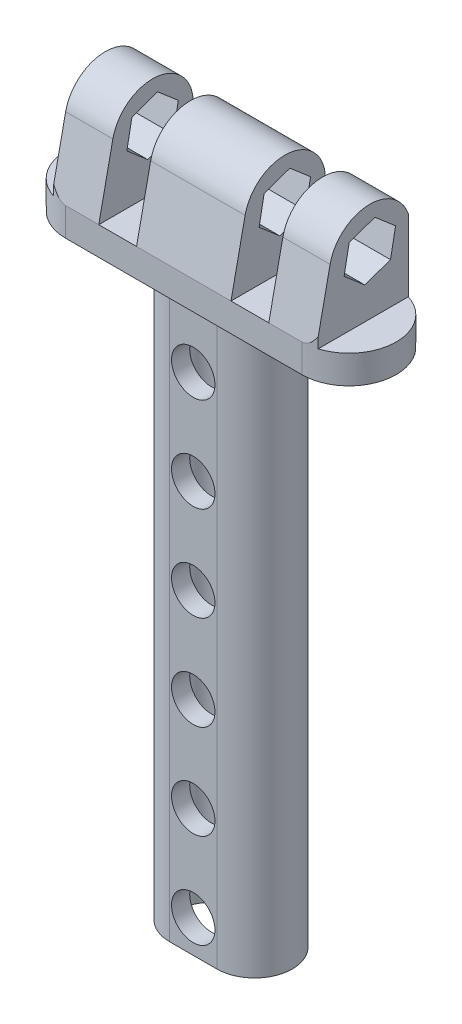
SolidWorks part; units mm, degrees
ref_plane "前视基准面" through (0, 0, 0) normal (0, 0, 1) x (1, 0, 0)
ref_plane "上视基准面" through (0, 0, 0) normal (0, 1, 0) x (1, 0, 0)
ref_plane "右视基准面" through (0, 0, 0) normal (1, 0, 0) x (0, 0, -1)
other "Configuration Table"
sketch "草图1" plane through (0, 0, 0) normal (0, 1, 0) x (1, 0, 0)
  line L0 (-12.5, 0) -> (12.5, 0) construction
  line L1 (-12.5, 5) -> (12.5, 5)
  line L2 (-12.5, -5) -> (12.5, -5)
  arc A0 (-12.5, 5) -> (-12.5, -5) centre (-12.5, 0) ccw
  arc A1 (12.5, -5) -> (12.5, 5) centre (12.5, 0) ccw
  point P2 (0, 0)
extrude "凸台-拉伸1" add sketch "草图1" along normal blind 3
sketch "草图2" plane through (0, 0, 0) normal (1, 0, 0) x (0, 0, -1)
  line L0 (-5, 3) -> (-3.5084, 10.1121)
  line L2 (5, 9.2295) -> (5, 3)
  line L3 (-5, 3) -> (5, 3)
  line L5 (2.889, 7.3476) -> (3.4243, 10.1843)
  line L6 (3.4243, 10.1843) -> (1.2353, 12.0662)
  line L7 (1.2353, 12.0662) -> (-1.489, 11.1114)
  line L8 (-1.489, 11.1114) -> (-2.0243, 8.2747)
  line L9 (-2.0243, 8.2747) -> (0.1648, 6.3928)
  line L10 (0.1648, 6.3928) -> (2.889, 7.3476)
  arc A1 (5, 9.2295) -> (-3.5084, 10.1121) centre (0.7, 9.2295) ccw
  circle A2 centre (0.7, 9.2295) radius 2.5 construction
  point P8 (5, 13.9205)
  point P16 (0, 0)
  point P17 (0, 0)
  point P18 (0, 0)
  dimension "D1" = 2.5
extrude "凸台-拉伸2" add sketch "草图2" along normal mid plane 28
sketch "草图3" plane through (0, 0, 0) normal (0, -1, 0) x (1, 0, 0)
  line L0 (-2.5, 0) -> (2.5, 0) construction
  line L1 (-2.5, 4) -> (2.5, 4)
  line L2 (-2.5, -4) -> (2.5, -4)
  line L3 (-2.7056, 0) -> (2.7056, 0) construction
  line L4 (-2.7056, 2.072) -> (2.7056, 2.072)
  line L5 (-2.7056, -2.072) -> (2.7056, -2.072)
  arc A0 (-2.5, 4) -> (-2.5, -4) centre (-2.5, 0) ccw
  arc A1 (2.5, -4) -> (2.5, 4) centre (2.5, 0) ccw
  arc A2 (-2.7056, 2.072) -> (-2.7056, -2.072) centre (-2.7056, 0) ccw
  arc A3 (2.7056, -2.072) -> (2.7056, 2.072) centre (2.7056, 0) ccw
  point P2 (0, 0)
  point P10 (0, 0)
  dimension "D1" = 8
  dimension "D2" = 5
extrude "凸台-拉伸3" add sketch "草图3" along normal blind 60
sketch "草图4" plane through (0, 0, 4) normal (0, 0, 1) x (1, 0, 0)
  circle A0 centre (0, -6.528) radius 2.3
  circle A1 centre (0, -16.528) radius 2.3
  circle A2 centre (0, -26.528) radius 2.3
  circle A3 centre (0, -36.528) radius 2.3
  circle A4 centre (0, -46.528) radius 2.3
  circle A5 centre (0, -56.528) radius 2.3
  dimension "D1" = 6
extrude "切除-拉伸1" cut sketch "草图4" against normal blind 60
sketch "草图6" plane through (0, 0, -5) normal (0, 0, -1) x (-1, 0, 0)
  line L0 (14, 13.5295) -> (-14, 13.5295) construction
  line L1 (-9, 13.5295) -> (-5, 13.5295)
  line L2 (-9, 13.5295) -> (-9, 3)
  line L3 (-9, 3) -> (-5, 3)
  line L4 (-5, 13.5295) -> (-5, 3)
  line L5 (-14, 3) -> (-12.5, 3) construction
  line L6 (0, 0) -> (0, 12.4747) construction
  line L7 (9, 3) -> (5, 3)
  line L8 (5, 13.5295) -> (5, 3)
  line L9 (9, 13.5295) -> (5, 13.5295)
  line L10 (9, 13.5295) -> (9, 3)
  dimension "D1" = 5
  dimension "D2" = 4
extrude "切除-拉伸2" cut sketch "草图6" against normal blind 60
sketch "草图7" plane through (0, 0, 0) normal (0, -1, 0) x (1, 0, 0)
  line L2 (-21.0201, 0) -> (21.0201, 0) construction
  line L3 (-21.0201, 8.0979) -> (21.0201, 8.0979)
  line L4 (-21.0201, -8.0979) -> (21.0201, -8.0979)
  line L13 (-12.5, -5) -> (12.5, -5)
  line L14 (12.5, 5) -> (-12.5, 5)
  line L15 (-12.5, -5) -> (12.5, -5)
  line L16 (12.5, 5) -> (-12.5, 5)
  arc A2 (-21.0201, 8.0979) -> (-21.0201, -8.0979) centre (-21.0201, 0) ccw
  arc A3 (21.0201, -8.0979) -> (21.0201, 8.0979) centre (21.0201, 0) ccw
  arc A10 (12.5, -5) -> (12.5, 5) centre (12.5, 0) ccw
  arc A11 (-12.5, 5) -> (-12.5, -5) centre (-12.5, 0) ccw
  arc A12 (12.5, -5) -> (12.5, 5) centre (12.5, 0) ccw
  arc A13 (-12.5, 5) -> (-12.5, -5) centre (-12.5, 0) ccw
  point P1 (0, 0)
  dimension "D1" = 0
extrude "切除-拉伸4" cut sketch "草图7" against normal blind 60
